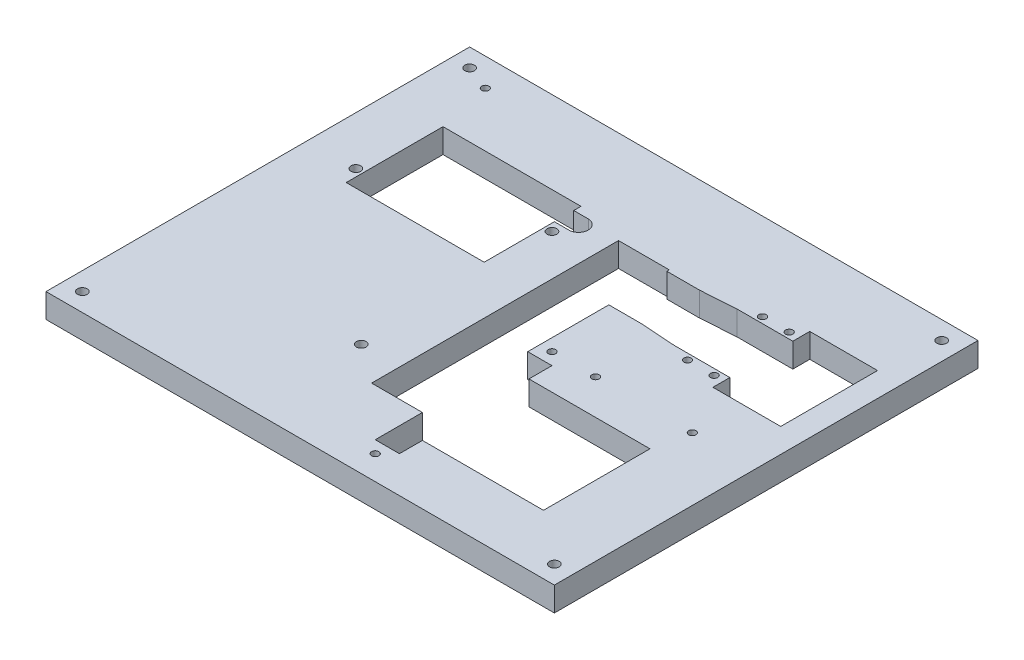
SolidWorks part; units mm, degrees
ref_plane "Спереди" through (0, 0, 0) normal (0, 0, 1) x (1, 0, 0)
ref_plane "Сверху" through (0, 0, 0) normal (0, 1, 0) x (1, 0, 0)
ref_plane "Справа" through (0, 0, 0) normal (1, 0, 0) x (0, 0, -1)
sketch "Эскиз1" plane through (0, 0, 0) normal (0, 1, 0) x (1, 0, 0)
  line L0 (0, 0) -> (53.9582, 0) construction
  line L1 (-5.5, 15.5) -> (5.5, 15.5) construction
  line L2 (-5.5, 15.5) -> (-5.5, -15.5) construction
  line L3 (-5.5, -15.5) -> (5.5, -15.5) construction
  line L4 (5.5, 15.5) -> (5.5, -15.5) construction
  line L5 (-5.5, 15.5) -> (5.5, -15.5) construction
  line L6 (-5.5, -15.5) -> (5.5, 15.5) construction
  line L7 (-13.5, 13) -> (-28, 12)
  line L8 (9.5, -20) -> (37.5, -20)
  line L9 (9.5, -20) -> (9.5, -13)
  line L10 (9.5, 20) -> (37.5, 20)
  line L11 (37.5, -20) -> (37.5, 20)
  line L12 (-36.5, 29.9259) -> (-36.5, -33.0741) construction
  line L13 (-50.3487, -77) -> (166.6351, -77) construction
  line L14 (-13.5, -13) -> (9.5, -13)
  line L16 (-13.5, 13) -> (9.5, 13)
  line L18 (-28, 12) -> (-28, -12) construction
  line L19 (-13.5, 13) -> (-13.5, -13) construction
  line L20 (-28, -12) -> (-41.5, -12)
  line L22 (-28, 12) -> (-41.5, 12)
  line L24 (-41.5, 10.4259) -> (-41.5, -13.5741) construction
  line L25 (-41.5, -45.5) -> (-41.5, -12)
  line L26 (-13.5, -13) -> (-28, -12)
  line L27 (9.5, 13) -> (9.5, 20)
  line L33 (-41.5, 13) -> (-62.5, 13)
  line L35 (18.5, -99) -> (-31.5, -99)
  line L36 (18.5, -99) -> (18.5, -55)
  line L37 (18.5, -55) -> (-31.5, -55)
  line L39 (-41.5, 12) -> (-41.5, 13)
  line L40 (-41.5, -108.5) -> (-41.5, -89)
  line L42 (-31.5, -55) -> (-31.5, -45.5)
  line L43 (-41.5, -108.5) -> (-31.5, -108.5)
  line L45 (-41.5, -45.5) -> (-31.5, -45.5)
  line L46 (-31.5, -108.5) -> (-31.5, -99)
  line L47 (-41.5, -89) -> (-62.5, -89)
  line L48 (-62.5, -89) -> (-62.5, 13)
  line L50 (-82.5, 17.5) -> (-82.5, 14.5)
  line L51 (-82.5, 17.5) -> (-139.5, 17.5)
  line L52 (-139.5, 17.5) -> (-139.5, -22.5)
  line L53 (-82.5, -22.5) -> (-139.5, -22.5)
  line L55 (-93.5183, -92.2452) -> (-63.5183, -92.2452) construction
  line L56 (-188.8257, -2.5) -> (-245.0227, -2.5) construction
  line L57 (-76.5, 14.5) -> (-82.5, 14.5)
  line L58 (-76.5, 6.5) -> (-82.5, 6.5)
  line L59 (-82.5, 6.5) -> (-82.5, -22.5)
  line L60 (-18.5, -40.5) -> (21.5, -40.5) construction
  line L61 (-162.5, 51.5) -> (47.5, 51.5)
  line L62 (-162.5, 51.5) -> (-162.5, -123.5)
  line L63 (-162.5, -123.5) -> (47.5, -123.5)
  line L64 (47.5, 51.5) -> (47.5, -123.5)
  line L65 (-160.4745, 44) -> (-62.9844, 44) construction
  line L66 (-155.5154, -116) -> (4.8455, -116) construction
  line L67 (-155, 67.9696) -> (-155, -182.0526) construction
  line L68 (40, -138.8386) -> (40, 94.6557) construction
  line L69 (-76.5, 14.5) -> (-76.5, 6.5) construction
  line L70 (-149.5, 32.5) -> (-139.5, 32.5) construction
  line L71 (-149.5, 32.5) -> (-149.5, 47.5) construction
  line L72 (-149.5, 47.5) -> (-139.5, 47.5) construction
  line L73 (-139.5, 32.5) -> (-139.5, 47.5) construction
  line L74 (-149.5, 32.5) -> (-139.5, 47.5) construction
  line L75 (-149.5, 47.5) -> (-139.5, 32.5) construction
  line L76 (-22.25, -45.5) -> (25.25, -45.5) construction
  line L77 (-22.25, -45.5) -> (-22.25, -35.5) construction
  line L78 (-22.25, -35.5) -> (25.25, -35.5) construction
  line L79 (25.25, -45.5) -> (25.25, -35.5) construction
  line L80 (-22.25, -45.5) -> (25.25, -35.5) construction
  line L81 (-22.25, -35.5) -> (25.25, -45.5) construction
  line L82 (-93.5183, -92.2452) -> (-93.5183, -62.2452) construction
  line L83 (-93.5183, -62.2452) -> (-63.5183, -62.2452) construction
  line L84 (-63.5183, -92.2452) -> (-63.5183, -62.2452) construction
  line L85 (-93.5183, -92.2452) -> (-63.5183, -62.2452) construction
  line L86 (-93.5183, -62.2452) -> (-63.5183, -92.2452) construction
  circle A0 centre (-5.5, 15.5) radius 1.5
  circle A1 centre (5.5, 15.5) radius 1.5
  circle A2 centre (-5.5, -15.5) radius 1.5
  circle A3 centre (5.5, -15.5) radius 1.5
  circle A4 centre (-36.5, -40.5) radius 1.5
  circle A5 centre (-36.5, -113.5) radius 1.5
  circle A6 centre (-144.5, 40) radius 1.5
  circle A7 centre (-79.5, 2.5) radius 2
  circle A8 centre (-142.5, -15.5) radius 2
  circle A10 centre (-18.5, -40.5) radius 1.5
  circle A11 centre (21.5, -40.5) radius 1.5
  circle A12 centre (-155, 44) radius 2
  circle A13 centre (40, 44) radius 2
  circle A14 centre (40, -116) radius 2
  circle A15 centre (-155, -116) radius 2
  arc A16 (-76.5, 6.5) -> (-76.5, 14.5) centre (-76.5, 10.5) ccw
  circle A17 centre (-78.5183, -77.2452) radius 2
  point P0 (0, 0)
  point P13 (-36.5, -45.5)
  point P19 (0, 0)
  point P44 (18.5, -77)
  point P51 (-78.5183, -77.2452)
  point P60 (-76.5, 10.5)
  point P81 (40, 44)
  point P83 (40, 44)
  point P85 (-155, -116)
  point P86 (40, -116)
  point P87 (-155, 44)
  point P100 (1.5, -40.5)
  point P101 (1.5, -40.5)
  point P109 (-72.5, 10.5)
  point P112 (0, 0)
  point P113 (-139.5, -2.5)
  point P114 (-87.0906, -56.8756)
  point P117 (-84.3453, -77.0371)
  point P118 (-78.5183, -77.2452)
  dimension "D4" = 150
  dimension "D5" = 40
  dimension "D6" = 3
  dimension "D27" = 28
  dimension "D33" = 3
  dimension "D34" = 3
  dimension "D30" = 4
  dimension "D36" = 6
  dimension "D42" = 3
  dimension "D50" = 4
  dimension "D63" = 4
  dimension "D1" = 31
  dimension "D2" = 11
  dimension "D7" = 4
  dimension "D8" = 23
  dimension "D9" = 13
  dimension "D10" = 13
  dimension "D11" = 14.5
  dimension "D12" = 44
  dimension "D13" = 12
  dimension "D14" = 12
  dimension "D15" = 77
  dimension "D16" = 63
  dimension "D17" = 47
  dimension "D18" = 1
  dimension "D19" = 10
  dimension "D20" = 50
  dimension "D21" = 21
  dimension "D22" = 12
  dimension "D23" = 57
  dimension "D24" = 40
  dimension "D25" = 5
  dimension "D26" = 13
  dimension "D28" = 20
  dimension "D29" = 20
  dimension "D31" = 5
  dimension "D32" = 5
  dimension "D35" = 3
  dimension "D37" = 3
  dimension "D38" = 13
  dimension "D39" = 15
  dimension "D40" = 175
  dimension "D41" = 210
  dimension "D43" = 40
  dimension "D44" = 25
  dimension "D45" = 24
  dimension "D46" = 7.5
  dimension "D47" = 7.5
  dimension "D48" = 7.5
  dimension "D49" = 7.5
  dimension "D51" = 15
  dimension "D52" = 10
  dimension "D53" = 10
  dimension "D54" = 47.5
  dimension "D55" = 4
  dimension "D56" = 13
  dimension "D57" = 10
  dimension "D58" = 10
  dimension "D59" = 10
  dimension "D60" = 90
  dimension "D61" = 30
  dimension "D62" = 30
extrude "Бобышка-Вытянуть1" add sketch "Эскиз1" along normal blind 10
